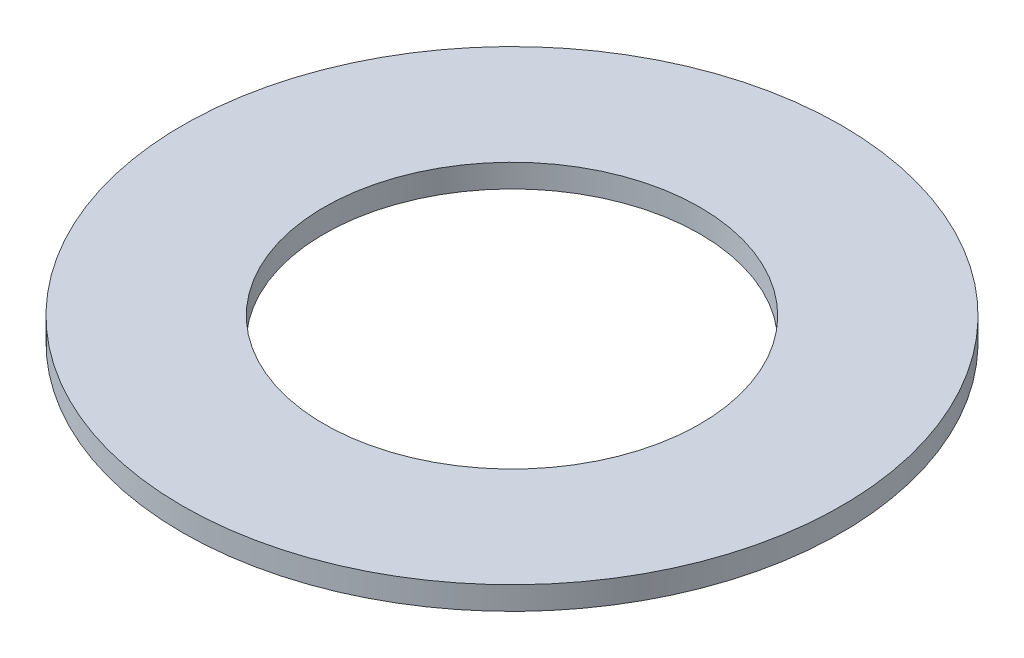
SolidWorks part; units mm, degrees
material "PETG"
ref_plane "Front Plane" through (0, 0, 0) normal (0, 0, 1) x (1, 0, 0)
ref_plane "Top Plane" through (0, 0, 0) normal (0, 1, 0) x (1, 0, 0)
ref_plane "Right Plane" through (0, 0, 0) normal (1, 0, 0) x (0, 0, -1)
sketch "Sketch1" plane through (0, 0, 0) normal (0, 0, 1) x (1, 0, 0)
  line L0 (0, 0) -> (0, 50000) construction
  line L2 (32.5, 2) -> (57, 2)
  line L3 (32.5, 2) -> (32.5, -2)
  line L4 (32.5, -2) -> (57, -2)
  line L5 (57, 2) -> (57, -2)
  point P7 (57, 0)
  dimension "D1" = 114
  dimension "D2" = 65
  dimension "D3" = 4
revolve "Revolve1" add sketch "Sketch1" angle 360 about L0
equation "\"CanSat_Len\"= 400mm"
equation "\"CanSat_Dia\"= 150mm"
equation "\"BodyTube_ID\"= 114mm"
equation "\"BodyTube_OD\"= 120mm"
equation "\"PayLoadBay_ID\"= 164mm"
equation "\"PayLoadBay_OD\"= 170mm"
equation "\"ParachuteBay_Pitch\"= 300mm"
equation "\"ElectronicsTray_PitchDist\"= 50mm"
equation "\"ElectronicsTray_Height\"= 140mm"
equation "\"MotorDia\"= 98mm"
equation "\"MotorLen\"=289mm"
equation "\"D1@Sketch1\"=\"BodyTube_ID\""
